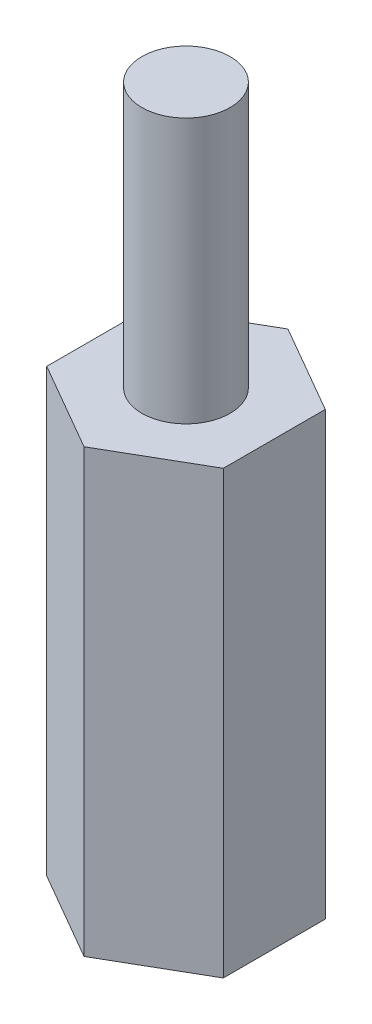
SolidWorks part; units mm, degrees
ref_plane "Спереди" through (0, 0, 0) normal (0, 0, 1) x (1, 0, 0)
ref_plane "Сверху" through (0, 0, 0) normal (0, 1, 0) x (1, 0, 0)
ref_plane "Справа" through (0, 0, 0) normal (1, 0, 0) x (0, 0, -1)
sketch "Эскиз1" plane through (0, 0, 0) normal (0, 1, 0) x (1, 0, 0)
  line L1 (0, -2.3094) -> (2, -1.1547)
  line L2 (2, -1.1547) -> (2, 1.1547)
  line L3 (2, 1.1547) -> (0, 2.3094)
  line L4 (0, 2.3094) -> (-2, 1.1547)
  line L5 (-2, 1.1547) -> (-2, -1.1547)
  line L6 (-2, -1.1547) -> (0, -2.3094)
  circle A0 centre (0, 0) radius 2 construction
  point P1 (0, 0)
  dimension "D1" = 4
extrude "Бобышка-Вытянуть1" add sketch "Эскиз1" along normal blind 10
sketch "Эскиз2" plane through (0, 10, 0) normal (0, 1, 0) x (1, 0, 0)
  circle A0 centre (0, 0) radius 1
  dimension "D1" = 2
extrude "Бобышка-Вытянуть2" add sketch "Эскиз2" along normal blind 6
